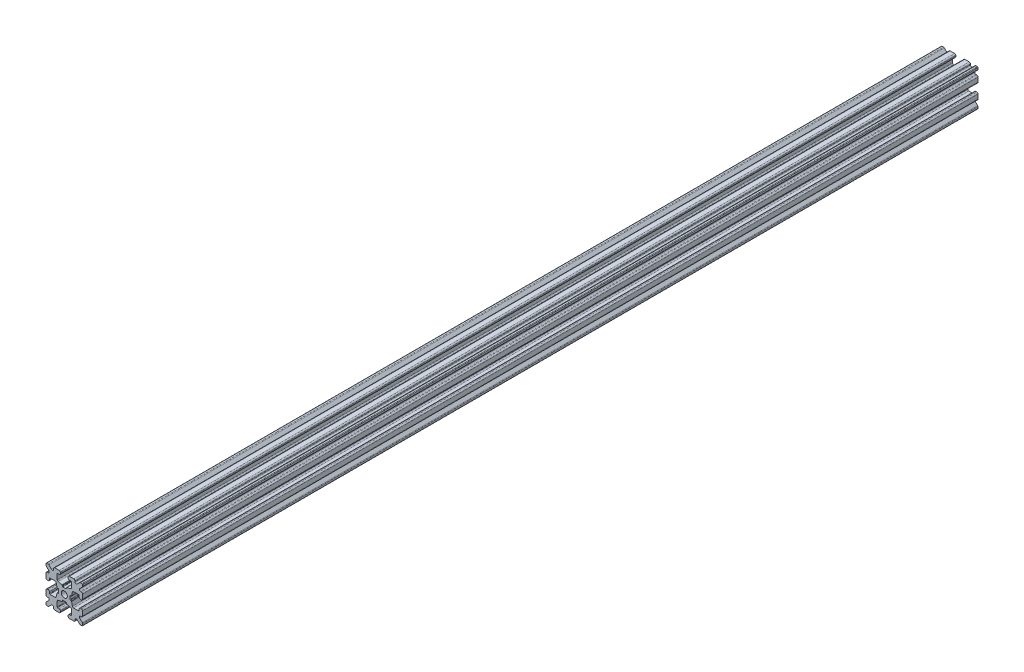
SolidWorks part; units mm, degrees
material "1060 Alloy"
ref_plane "Front Plane" through (0, 0, 0) normal (0, 0, 1) x (1, 0, 0)
ref_plane "Top Plane" through (0, 0, 0) normal (0, 1, 0) x (1, 0, 0)
ref_plane "Right Plane" through (0, 0, 0) normal (1, 0, 0) x (0, 0, -1)
sketch "Sketch1" plane through (0, 0, 0) normal (0, 0, 1) x (1, 0, 0)
  line L1 (-7.5, -7.5) -> (7.5, -7.5)
  line L2 (-7.5, -7.5) -> (-7.5, 7.5)
  line L3 (-7.5, 7.5) -> (7.5, 7.5)
  line L4 (7.5, -7.5) -> (7.5, 7.5)
  line L5 (-7.5, -7.5) -> (7.5, 7.5) construction
  line L6 (-7.5, 7.5) -> (7.5, -7.5) construction
  circle A0 centre (0, 0) radius 1.25
  point P0 (0, 0)
  dimension "D2" = 2.5
  dimension "D1" = 15
extrude "Boss-Extrude1" add sketch "Sketch1" along normal mid plane 367
fillet "Fillet1" radius 0.25 4 edges at (7.5, -7.5, 0) (-7.5, -7.5, 0) (7.5, 7.5, 0) (-7.5, 7.5, 0)
sketch "Sketch2" plane through (0, 0, 183.5) normal (0, 0, 1) x (1, 0, 0)
  line L0 (-7.5, 7.25) -> (-7.5, -7.25) construction
  line L1 (-7.5, 1.6) -> (-6.1, 1.6)
  line L2 (-7.5, 1.6) -> (-7.5, -1.6)
  line L3 (-7.5, -1.6) -> (-6.1, -1.6)
  line L4 (-6.1, 1.6) -> (-6.1, 2.9)
  line L5 (0, 0) -> (-12.1036, 0) construction
  line L6 (-6.1, -2.9) -> (-3.4, -2.9)
  line L7 (0, 0) -> (-7.25, 7.25) construction
  line L8 (-6.1, 2.9) -> (-3.4, 2.9)
  line L9 (-3.4, -2.9) -> (-3.4, 2.9)
  line L10 (55, 0) -> (-55, 0) construction
  line L11 (-6.1, -2.9) -> (-6.1, -1.6)
  line L12 (2.9, 6.1) -> (1.6, 6.1)
  line L13 (2.9, 3.4) -> (-2.9, 3.4)
  line L14 (-2.9, 6.1) -> (-2.9, 3.4)
  line L15 (2.9, 6.1) -> (2.9, 3.4)
  line L16 (-1.6, 6.1) -> (-2.9, 6.1)
  line L17 (1.6, 7.5) -> (1.6, 6.1)
  line L18 (-1.6, 7.5) -> (1.6, 7.5)
  line L19 (-1.6, 7.5) -> (-1.6, 6.1)
  line L20 (-1.6, -7.5) -> (-1.6, -6.1)
  line L21 (-1.6, -7.5) -> (1.6, -7.5)
  line L22 (1.6, -7.5) -> (1.6, -6.1)
  line L23 (-1.6, -6.1) -> (-2.9, -6.1)
  line L24 (2.9, -6.1) -> (2.9, -3.4)
  line L25 (-2.9, -6.1) -> (-2.9, -3.4)
  line L26 (2.9, -3.4) -> (-2.9, -3.4)
  line L27 (2.9, -6.1) -> (1.6, -6.1)
  line L28 (6.1, -2.9) -> (6.1, -1.6)
  line L29 (3.4, -2.9) -> (3.4, 2.9)
  line L30 (6.1, 2.9) -> (3.4, 2.9)
  line L31 (6.1, -2.9) -> (3.4, -2.9)
  line L32 (6.1, 1.6) -> (6.1, 2.9)
  line L33 (7.5, -1.6) -> (6.1, -1.6)
  line L34 (7.5, 1.6) -> (7.5, -1.6)
  line L35 (7.5, 1.6) -> (6.1, 1.6)
  dimension "D1" = 3.2
  dimension "D2" = 5.8
  dimension "D3" = 1.4
  dimension "D4" = 2.7
extrude "Cut-Extrude1" cut sketch "Sketch2" against normal through all
sketch "Sketch4" plane through (0, 0, 183.5) normal (0, 0, 1) x (1, 0, 0)
  line L0 (-3.4, 2.9) -> (-2.75, 0)
  line L1 (55, 0) -> (-55, 0) construction
  line L2 (-2.75, 0) -> (-3.4, -2.9)
  line L3 (-3.4, -2.9) -> (-3.4, 2.9) construction
  line L4 (-3.4, 2.9) -> (-3.4, -2.9)
  line L5 (-2.9, 3.4) -> (0, 2.75)
  line L6 (0, 2.75) -> (2.9, 3.4)
  line L7 (2.9, 3.4) -> (-2.9, 3.4)
  line L8 (3.4, 2.9) -> (2.75, 0)
  line L9 (2.75, 0) -> (3.4, -2.9)
  line L10 (3.4, -2.9) -> (3.4, 2.9)
  line L11 (-2.9, -3.4) -> (0, -2.75)
  line L12 (0, -2.75) -> (2.9, -3.4)
  line L13 (2.9, -3.4) -> (-2.9, -3.4)
  circle A2 centre (0, 0) radius 2.75
  circle A3 centre (0, 0) radius 2.75 construction
  dimension "D1" = 1.5
extrude "Cut-Extrude3" cut sketch "Sketch4" against normal through all
fillet "Fillet3" radius 0.5 16 edges at (-6.1, -1.6, 0) (-7.5, -1.6, 0) (-6.1, 1.6, 0) (-7.5, 1.6, 0) (-1.6, -7.5, 0) (-1.6, -6.1, 0) (1.6, -7.5, 0) (1.6, -6.1, 0) (6.1, -1.6, 0) (7.5, -1.6, 0) (7.5, 1.6, 0) (6.1, 1.6, 0) (1.6, 7.5, 0) (1.6, 6.1, 0) (-1.6, 7.5, 0) (-1.6, 6.1, 0)
fillet "Fillet4" radius 0.5 8 edges at (-3.4, 2.9, 0) (-3.4, -2.9, 0) (2.9, -3.4, 0) (-2.9, -3.4, 0) (3.4, -2.9, 0) (3.4, 2.9, 0) (-2.9, 3.4, 0) (2.9, 3.4, 0)
fillet "Fillet5" radius 3 4 edges at (0, -2.75, 0) (2.75, 0, 0) (-2.75, 0, 0) (0, 2.75, 0)
fillet "Fillet6" radius 0.2 8 edges at (-2.9, -6.1, 0) (2.9, -6.1, 0) (6.1, -2.9, 0) (6.1, 2.9, 0) (2.9, 6.1, 0) (-2.9, 6.1, 0) (-6.1, -2.9, 0) (-6.1, 2.9, 0)
sketch "Sketch5" plane through (0, 0, 183.5) normal (0, 0, 1) x (1, 0, 0)
  line L0 (0, 0) -> (-7.25, 7.25) construction
  line L1 (-7.5, 6.4393) -> (-5.4607, 4.4)
  line L2 (-6.4393, 7.5) -> (-4.4, 5.4607)
  line L3 (-7.5, 4.4) -> (-5.4607, 4.4)
  line L4 (-3.8003, 2.9) -> (-5.9, 2.9) construction
  line L5 (0, 0) -> (-12.1819, 0) construction
  line L6 (-4.4, 7.5) -> (-4.4, 5.4607)
  line L7 (-2.9, 5.9) -> (-2.9, 3.8003) construction
  line L8 (-7.5, 6.4393) -> (-7.5, 4.4)
  line L9 (-7.5, 7.25) -> (-7.5, 2.1) construction
  line L10 (2.1, -7.5) -> (7.25, -7.5) construction
  line L11 (7.5, -7.25) -> (7.5, -2.1) construction
  line L12 (7.25, 7.5) -> (2.1, 7.5) construction
  line L13 (-2.1, 7.5) -> (-7.25, 7.5) construction
  line L14 (-4.4, 7.5) -> (-6.4393, 7.5)
  line L16 (55, 0) -> (-55, 0) construction
  line L17 (0, 0) -> (0, 10.993) construction
  line L18 (0, -54.6431) -> (0, 54.6431) construction
  line L20 (4.4, 7.5) -> (6.4393, 7.5)
  line L22 (7.5, 6.4393) -> (7.5, 4.4)
  line L23 (4.4, 7.5) -> (4.4, 5.4607)
  line L24 (7.5, 4.4) -> (5.4607, 4.4)
  line L25 (6.4393, 7.5) -> (4.4, 5.4607)
  line L26 (7.5, 6.4393) -> (5.4607, 4.4)
  line L27 (7.5, -6.4393) -> (5.4607, -4.4)
  line L28 (6.4393, -7.5) -> (4.4, -5.4607)
  line L29 (7.5, -4.4) -> (5.4607, -4.4)
  line L30 (4.4, -7.5) -> (4.4, -5.4607)
  line L31 (7.5, -6.4393) -> (7.5, -4.4)
  line L33 (4.4, -7.5) -> (6.4393, -7.5)
  line L36 (-4.4, -7.5) -> (-6.4393, -7.5)
  line L38 (-7.5, -6.4393) -> (-7.5, -4.4)
  line L39 (-4.4, -7.5) -> (-4.4, -5.4607)
  line L40 (-7.5, -4.4) -> (-5.4607, -4.4)
  line L41 (-6.4393, -7.5) -> (-4.4, -5.4607)
  line L42 (-7.5, -6.4393) -> (-5.4607, -4.4)
  dimension "D1" = 1.5
  dimension "D2" = 1.5
  dimension "D3" = 1.5
extrude "Cut-Extrude4" cut sketch "Sketch5" against normal through all
fillet "Fillet8" radius 0.5 24 edges at (-5.4607, 4.4, 0) (-7.5, 4.4, 0) (-5.4607, -4.4, 0) (-7.5, -4.4, 0) (-4.4, -7.5, 0) (-4.4, -5.4607, 0) (4.4, -7.5, 0) (4.4, -5.4607, 0) (5.4607, -4.4, 0) (7.5, -4.4, 0) (7.5, 4.4, 0) (5.4607, 4.4, 0) (4.4, 5.4607, 0) (4.4, 7.5, 0) (-4.4, 5.4607, 0) (-4.4, 7.5, 0) (-6.4393, 7.5, 0) (-7.5, 6.4393, 0) (6.4393, 7.5, 0) (7.5, 6.4393, 0) (6.4393, -7.5, 0) (7.5, -6.4393, 0) (-6.4393, -7.5, 0) (-7.5, -6.4393, 0)
sketch "Sketch6" plane through (0, 0, 183.5) normal (0, 0, 1) x (1, 0, 0)
  line L0 (0, 0) -> (0, 11.013) construction
  line L1 (0.6561, 2.8971) -> (2.1235, 2.8971) construction
  line L2 (0, -54.6431) -> (0, 54.6431) construction
  line L3 (0, 0) -> (7.25, 7.25) construction
  line L4 (7.5, 0.8255) -> (7.5, -0.8255)
  line L5 (2.3471, 0.8255) -> (7.5, 0.8255)
  line L6 (0, 0) -> (12.4016, 0) construction
  line L7 (0.8255, -7.5) -> (-0.8255, -7.5)
  line L8 (2.3471, -0.8255) -> (2.3471, 0.8255)
  line L9 (0.8255, -2.3471) -> (0.8255, -7.5)
  line L10 (7.5, -0.8255) -> (2.3471, -0.8255)
  line L11 (-7.5, -0.8255) -> (-2.3471, -0.8255)
  line L12 (-2.3471, -0.8255) -> (-2.3471, 0.8255)
  line L13 (-0.8255, -2.3471) -> (0.8255, -2.3471)
  line L14 (-0.8255, 7.5) -> (-0.8255, 2.3471)
  line L15 (-0.8255, 2.3471) -> (0.8255, 2.3471)
  line L16 (-0.8255, -7.5) -> (-0.8255, -2.3471)
  line L17 (0.8255, 2.3471) -> (0.8255, 7.5)
  line L18 (0.8255, 7.5) -> (-0.8255, 7.5)
  line L19 (3.9, 7.5) -> (2.1, 7.5) construction
  line L20 (-2.3471, 0.8255) -> (-7.5, 0.8255)
  line L21 (-7.5, 0.8255) -> (-7.5, -0.8255)
  point P5 (0, -2.5973)
  point P7 (0, 2.5973)
  dimension "D3" = 0.55
  dimension "D1" = 1.651
extrude "Cut-Extrude5" cut sketch "Sketch6" against normal through all
fillet "Fillet10" radius 0.2 16 edges at (-2.935, 0.8255, 0) (-2.935, -0.8255, 0) (2.935, -0.8255, 0) (2.935, 0.8255, 0) (0.8255, 2.935, 0) (-0.8255, 2.935, 0) (-2.3471, 0.8255, 0) (-2.3471, -0.8255, 0) (0.8255, 2.3471, 0) (-0.8255, 2.3471, 0) (2.3471, 0.8255, 0) (2.3471, -0.8255, 0) (0.8255, -2.935, 0) (0.8255, -2.3471, 0) (-0.8255, -2.3471, 0) (-0.8255, -2.935, 0)
